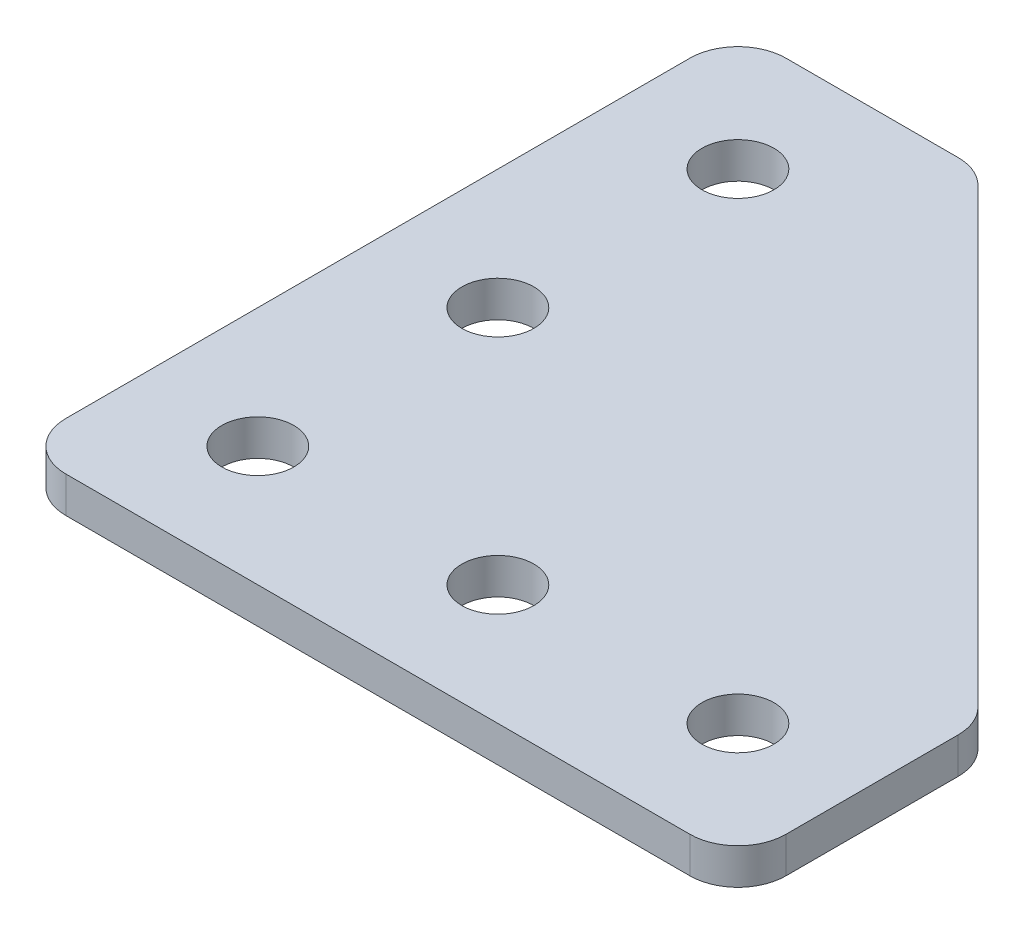
SolidWorks part; units mm, degrees
material "1060 合金"
ref_plane "正面" through (0, 0, 0) normal (0, 0, 1) x (1, 0, 0)
ref_plane "平面" through (0, 0, 0) normal (0, 1, 0) x (1, 0, 0)
ref_plane "右側面" through (0, 0, 0) normal (1, 0, 0) x (0, 0, -1)
sketch "ｽｹｯﾁ2" plane through (0, 0, 0) normal (0, 1, 0) x (1, 0, 0)
  line L0 (0, 0) -> (30, 0)
  line L1 (30, 0) -> (30, 10)
  line L2 (30, 10) -> (10, 30)
  line L3 (10, 30) -> (0, 30)
  line L4 (0, 30) -> (0, 0)
  line L5 (0, 0) -> (20, 20) construction
  line L6 (30, 5) -> (0, 5) construction
  circle A0 centre (5, 5) radius 1.5
  circle A1 centre (25, 5) radius 1.5
  circle A2 centre (5, 25) radius 1.5
  circle A3 centre (15, 5) radius 1.5
  circle A4 centre (5, 15) radius 1.5
  dimension "D1" = 10
  dimension "D2" = 3
  dimension "D3" = 5
  dimension "D4" = 5
  dimension "D5" = 20
  dimension "D6" = 10
  dimension "D7" = 10
extrude "ﾎﾞｽ - 押し出し1" add sketch "ｽｹｯﾁ2" along normal blind 1.5
fillet "ﾌｨﾚｯﾄ1" radius 2 5 edges at (0, 0.75, 0) (30, 0.75, 0) (30, 0.75, -10) (10, 0.75, -30) (0, 0.75, -30)
